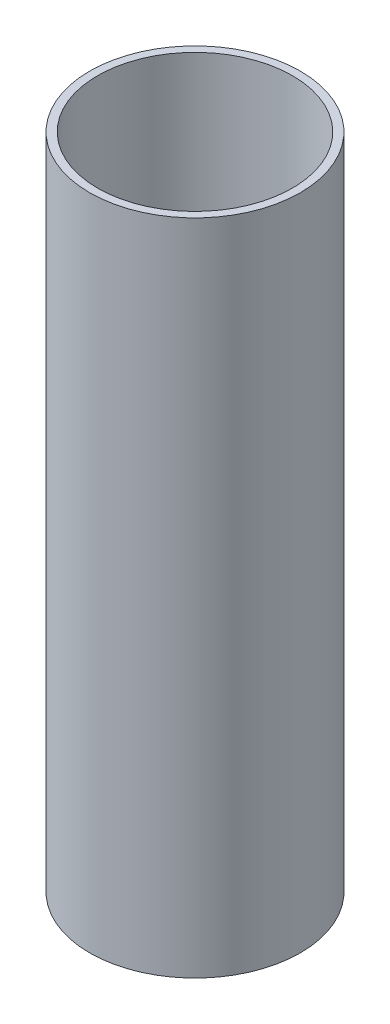
SolidWorks part; units mm, degrees
ref_plane "Front Plane" through (0, 0, 0) normal (0, 0, 1) x (1, 0, 0)
ref_plane "Top Plane" through (0, 0, 0) normal (0, 1, 0) x (1, 0, 0)
ref_plane "Right Plane" through (0, 0, 0) normal (1, 0, 0) x (0, 0, -1)
sketch "Sketch1" plane through (0, 0, 0) normal (0, 1, 0) x (1, 0, 0)
  circle A0 centre (0, 0) radius 16
  circle A1 centre (0, 0) radius 14.8
  dimension "D1" = 1.2
  dimension "D2" = 32
extrude "Boss-Extrude1" add sketch "Sketch1" along normal blind 100
sketch "Sketch2" plane through (0, 0, 0) normal (1, 0, 0) x (0, 0, -1)
  line L0 (0, 0) -> (0, 100) construction
  line L1 (16, 100) -> (-16, 100) construction
  circle A0 centre (0, 50) radius 3.25
  point P8 (0, 50)
  dimension "D1" = 6.5
extrude "Cut-Extrude1" cut sketch "Sketch2" against normal through all
